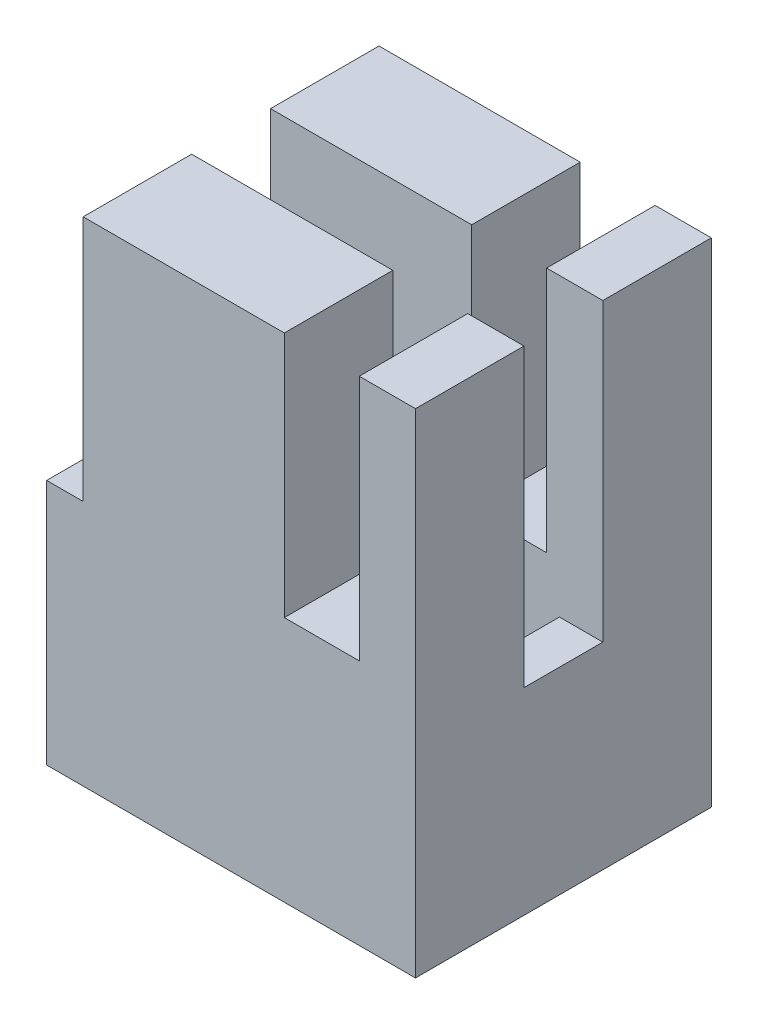
SolidWorks part; units mm, degrees
ref_plane "Front Plane" through (0, 0, 0) normal (0, 0, 1) x (1, 0, 0)
ref_plane "Top Plane" through (0, 0, 0) normal (0, 1, 0) x (1, 0, 0)
ref_plane "Right Plane" through (0, 0, 0) normal (1, 0, 0) x (0, 0, -1)
sketch "Sketch1" plane through (0, 0, 0) normal (0, 1, 0) x (1, 0, 0)
  line L1 (-23.749, 19.05) -> (23.749, 19.05)
  line L2 (-23.749, 19.05) -> (-23.749, -19.05)
  line L3 (-23.749, -19.05) -> (23.749, -19.05)
  line L4 (23.749, 19.05) -> (23.749, -19.05)
  line L5 (-23.749, 19.05) -> (23.749, -19.05) construction
  line L6 (-23.749, -19.05) -> (23.749, 19.05) construction
  point P0 (0, 0)
  dimension "D1" = 38.1
  dimension "D2" = 47.498
extrude "Boss-Extrude1" add sketch "Sketch1" along normal blind 63.5
sketch "Sketch3" plane through (0, 63.5, 0) normal (0, 1, 0) x (1, 0, 0)
  line L0 (23.749, -19.05) -> (23.749, 19.05) construction
  line L1 (-23.749, 5.08) -> (23.749, 5.08)
  line L2 (-23.749, 5.08) -> (-23.749, -5.08)
  line L3 (-23.749, -5.08) -> (23.749, -5.08)
  line L4 (23.749, 5.08) -> (23.749, -5.08)
  line L5 (-23.749, 5.08) -> (23.749, -5.08) construction
  line L6 (-23.749, -5.08) -> (23.749, 5.08) construction
  point P0 (0, 0)
  dimension "D1" = 10.16
extrude "Cut-Extrude1" cut sketch "Sketch3" against normal blind 38.1
sketch "Sketch4" plane through (0, 0, 0) normal (0, -1, 0) x (1, 0, 0)
  line L0 (-23.749, -19.05) -> (-23.749, 19.05) construction
  line L1 (-23.749, -8.5725) -> (18.161, -8.5725)
  line L2 (-23.749, -8.5725) -> (-23.749, 8.5725)
  line L3 (-23.749, 8.5725) -> (18.161, 8.5725)
  line L4 (18.161, -8.5725) -> (18.161, 8.5725)
  line L5 (-23.749, -8.5725) -> (18.161, 8.5725) construction
  line L6 (-23.749, 8.5725) -> (18.161, -8.5725) construction
  line L7 (23.749, 19.05) -> (23.749, -19.05) construction
  line L8 (-23.749, 8.5725) -> (-23.749, 19.05) construction
  line L9 (-23.749, -8.5725) -> (-23.749, -19.05) construction
  point P0 (-2.794, 0)
  dimension "D1" = 17.145
  dimension "D2" = 5.588
extrude "Cut-Extrude2" cut sketch "Sketch4" against normal offset from surface (19.05 mm away) 6.35 up to face at (0, 25.4, 0)
sketch "Sketch5" plane through (0, 25.4, 0) normal (0, 1, 0) x (1, 0, 0)
  line L1 (-21.971, -5.08) -> (18.161, -5.08)
  line L2 (-21.971, -5.08) -> (-21.971, 5.08)
  line L3 (-21.971, 5.08) -> (18.161, 5.08)
  line L4 (18.161, -5.08) -> (18.161, 5.08)
  line L5 (-21.971, -5.08) -> (18.161, 5.08) construction
  line L6 (-21.971, 5.08) -> (18.161, -5.08) construction
  line L7 (-21.971, 5.08) -> (-23.749, 5.08) construction
  line L8 (23.749, -5.08) -> (23.749, 5.08) construction
  point P0 (-1.905, 0)
  dimension "D1" = 1.778
  dimension "D2" = 5.588
extrude "Cut-Extrude3" cut sketch "Sketch5" against normal through all
sketch "Sketch6" plane through (0, 63.5, 0) normal (0, 1, 0) x (1, 0, 0)
  line L0 (-23.749, -19.05) -> (23.749, -19.05) construction
  line L1 (16.51, 19.05) -> (6.858, 19.05)
  line L2 (16.51, 19.05) -> (16.51, -19.05)
  line L3 (16.51, -19.05) -> (6.858, -19.05)
  line L4 (6.858, 19.05) -> (6.858, -19.05)
  line L6 (-23.749, 19.05) -> (-19.05, 19.05)
  line L7 (-23.749, 19.05) -> (-23.749, -19.05)
  line L8 (-23.749, -19.05) -> (-19.05, -19.05)
  line L9 (-19.05, 19.05) -> (-19.05, -19.05)
  line L12 (23.749, 19.05) -> (-23.749, 19.05) construction
  line L13 (23.749, 5.08) -> (23.749, 19.05) construction
  point P14 (0, 0)
  dimension "D1" = 9.652
  dimension "D2" = 4.699
  dimension "D3" = 7.239
extrude "Cut-Extrude4" cut sketch "Sketch6" against normal offset from surface (31.75 mm away) 6.35 up to face at (-22.86, 25.4, 0)
